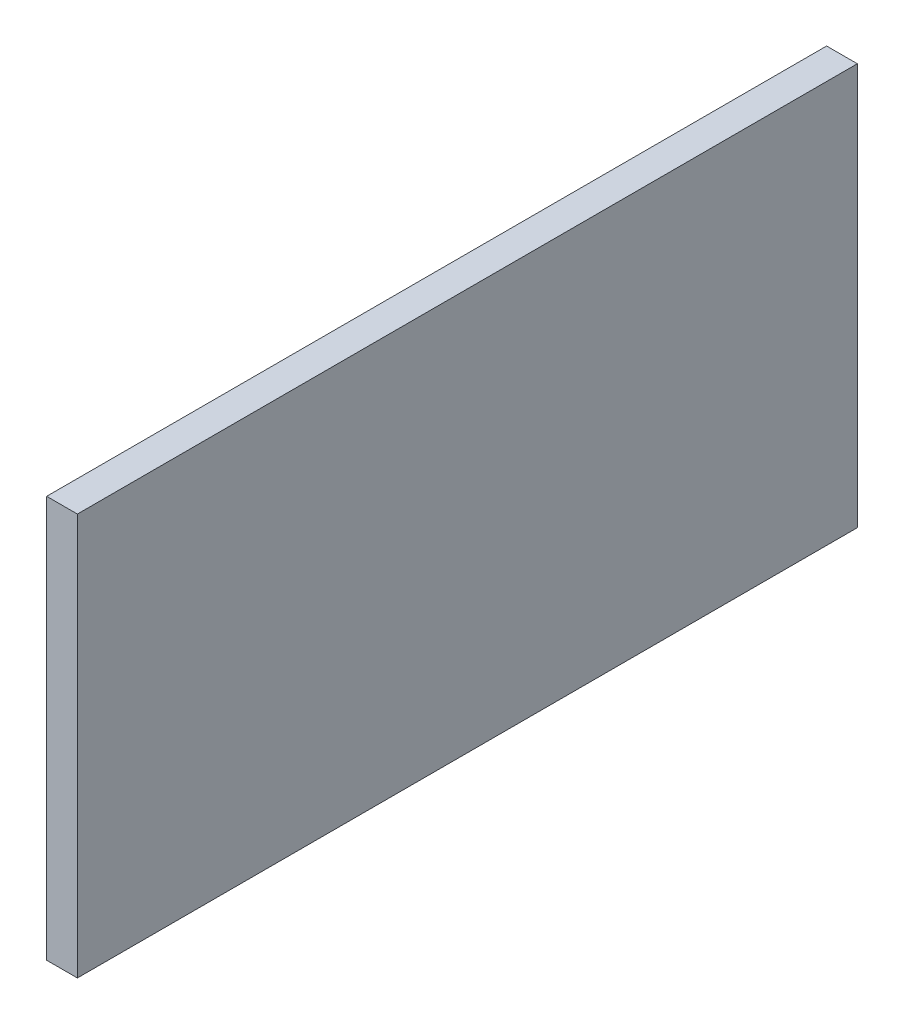
SolidWorks part; units mm, degrees
ref_plane "Front Plane" through (0, 0, 0) normal (0, 0, 1) x (1, 0, 0)
ref_plane "Top Plane" through (0, 0, 0) normal (0, 1, 0) x (1, 0, 0)
ref_plane "Right Plane" through (0, 0, 0) normal (1, 0, 0) x (0, 0, -1)
sketch "Sketch1" plane through (0, 0, 0) normal (1, 0, 0) x (0, 0, -1)
  line L1 (-16.5, -8.5) -> (16.5, -8.5)
  line L2 (-16.5, -8.5) -> (-16.5, 8.5)
  line L3 (-16.5, 8.5) -> (16.5, 8.5)
  line L4 (16.5, -8.5) -> (16.5, 8.5)
  line L5 (-16.5, -8.5) -> (16.5, 8.5) construction
  line L6 (-16.5, 8.5) -> (16.5, -8.5) construction
  point P0 (0, 0)
  dimension "D1" = 33
  dimension "D2" = 17
extrude "Boss-Extrude1" add sketch "Sketch1" along normal blind 1.3
